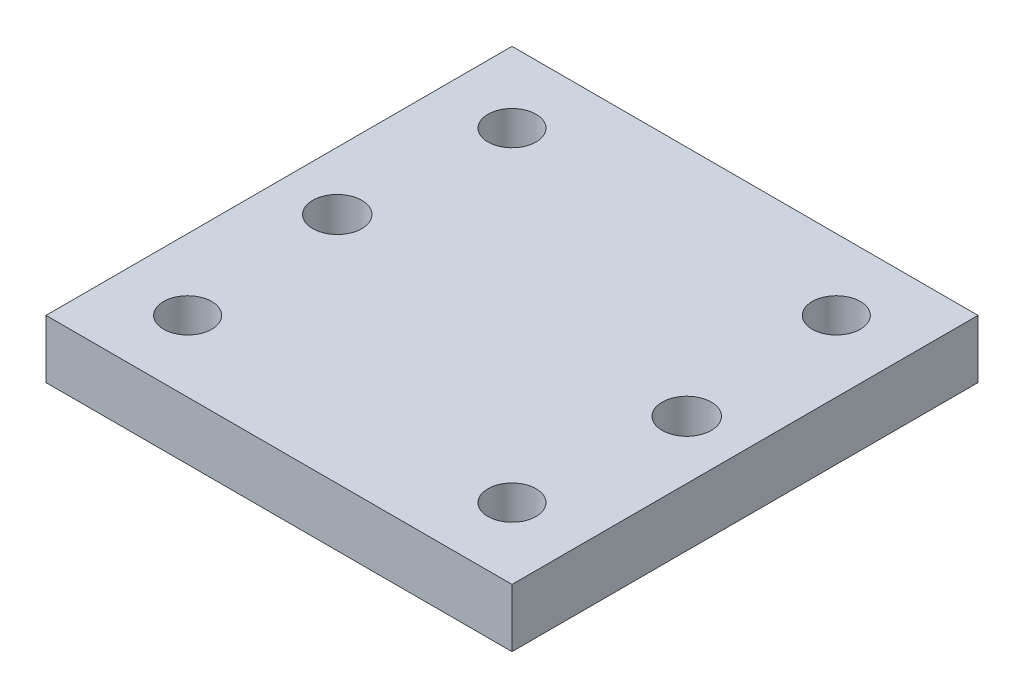
SolidWorks part; units mm, degrees
ref_plane "Front Plane" through (0, 0, 0) normal (0, 0, 1) x (1, 0, 0)
ref_plane "Top Plane" through (0, 0, 0) normal (0, 1, 0) x (1, 0, 0)
ref_plane "Right Plane" through (0, 0, 0) normal (1, 0, 0) x (0, 0, -1)
sketch "Sketch1" plane through (0, 0, 0) normal (0, 1, 0) x (1, 0, 0)
  line L1 (0, 0) -> (101.6, 0)
  line L2 (0, 0) -> (0, 101.6)
  line L3 (0, 101.6) -> (101.6, 101.6)
  line L4 (101.6, 0) -> (101.6, 101.6)
  dimension "D1" = 101.6
  dimension "D2" = 101.6
extrude "Boss-Extrude1" add sketch "Sketch1" along normal blind 12.7
hole_wizard "M10 Clearance Hole1" positions "Sketch2" profile "Sketch3" hole size "M10" standard "ANSI Metric" end condition through all
sketch "Sketch2" plane through (0, 12.7, 0) normal (0, 1, 0) x (1, 0, 0)
  line L0 (0, 50.8) -> (101.6, 50.8) construction
  line L1 (0, 101.6) -> (0, 0) construction
  line L2 (101.6, 0) -> (101.6, 101.6) construction
  line L3 (50.8, 50.8) -> (86.1553, 86.1553) construction
  line L4 (50.8, 50.8) -> (50.8, 0) construction
  line L5 (0, 0) -> (101.6, 0) construction
  circle A0 centre (50.8, 50.8) radius 50 construction
  point P0 (86.1553, 86.1553)
  point P26 (86.1553, 15.4447)
  point P33 (15.4447, 86.1553)
  point P34 (15.4447, 15.4447)
  dimension "D2" = 100
  dimension "D1" = 45
sketch "Sketch3" plane through (86.1553, 12.7, -86.1553) normal (1, 0, 0) x (0, 0, 1)
  line L0 (0, 0) -> (0, 12.7)
  line L1 (0, 12.7) -> (5.25, 12.7)
  line L2 (5.25, 12.7) -> (5.25, 0)
  line L5 (5.25, 0) -> (0, 0)
  line L11 (0, -6.35) -> (0, 107.95) construction
  dimension "Thru Hole Dia." = 10.5
  dimension "Thru Hole Depth" = 12.7
hole_wizard "1/2-13 Tapped Hole1" positions "Sketch4" profile "Sketch5" tap size "1/2-13" standard "ANSI Inch" end condition through all
sketch "Sketch4" plane through (0, 12.7, 0) normal (0, 1, 0) x (1, 0, 0)
  line L0 (0, 50.8) -> (101.6, 50.8) construction
  line L1 (0, 101.6) -> (0, 0) construction
  line L2 (101.6, 0) -> (101.6, 101.6) construction
  line L3 (50.8, 101.6) -> (50.8, 0) construction
  line L4 (101.6, 101.6) -> (0, 101.6) construction
  line L5 (0, 0) -> (101.6, 0) construction
  point P0 (88.9, 50.8)
  point P2 (12.7, 50.8)
  dimension "D1" = 76.2
  dimension "D2" = 38.1
sketch "Sketch5" plane through (88.9, 12.7, -50.8) normal (1, 0, 0) x (0, 0, 1)
  line L0 (0, 0) -> (0, 12.7)
  line L1 (0, 12.7) -> (5.3581, 12.7)
  line L2 (5.3581, 12.7) -> (5.3581, 0)
  line L5 (5.3581, 0) -> (0, 0)
  line L11 (0, -6.35) -> (0, 107.95) construction
  dimension "Thru Tap Drill Dia." = 10.7163
  dimension "Thru Tap Drill Depth" = 12.7
cosmetic thread "Hole Thread1" parameters "D2"=12.7
cosmetic thread "Hole Thread2" parameters "D2"=12.7
